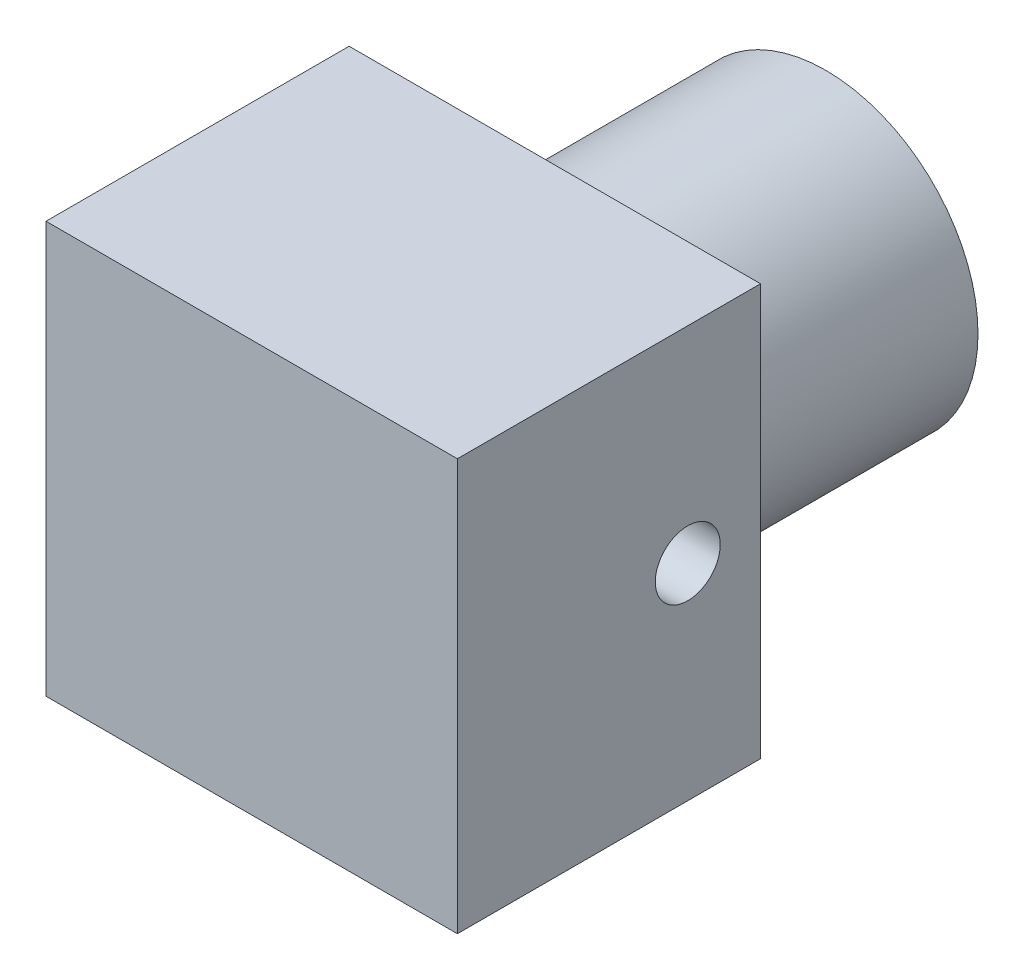
SolidWorks part; units mm, degrees
ref_plane "前视基准面" through (0, 0, 0) normal (0, 0, 1) x (1, 0, 0)
ref_plane "上视基准面" through (0, 0, 0) normal (0, 1, 0) x (1, 0, 0)
ref_plane "右视基准面" through (0, 0, 0) normal (1, 0, 0) x (0, 0, -1)
other "Configuration Table"
sketch "草图1" plane through (0, 0, 0) normal (0, 0, 1) x (1, 0, 0)
  circle A0 centre (0, 0) radius 7.025
  dimension "D1" = 14.05
extrude "凸台-拉伸1" add sketch "草图1" along normal blind 12.52
sketch "草图2" plane through (0, 0, 12.52) normal (0, 0, 1) x (1, 0, 0)
  line L0 (0, 0) -> (9.5, 9.5) construction
  line L1 (-9.5, -9.5) -> (9.5, -9.5)
  line L2 (-9.5, -9.5) -> (-9.5, 9.5)
  line L3 (-9.5, 9.5) -> (9.5, 9.5)
  line L4 (9.5, -9.5) -> (9.5, 9.5)
  line L5 (-9.5, -9.5) -> (-4.9674, -4.9674) construction
  line L6 (-9.5, 9.5) -> (0, 0) construction
  line L7 (4.9674, -4.9674) -> (9.5, -9.5) construction
  dimension "D2" = 19
  dimension "D3" = 19
extrude "凸台-拉伸2" add sketch "草图2" along normal blind 14
sketch "草图3" plane through (-9.5, 0, 0) normal (-1, 0, 0) x (0, 0, 1)
  line L0 (12.52, 0) -> (15.88, 0)
  line L4 (12.52, 9.5) -> (12.52, -9.5)
  line L5 (12.52, -9.5) -> (26.52, -9.5)
  line L6 (26.52, -9.5) -> (26.52, 9.5)
  line L7 (26.52, 9.5) -> (12.52, 9.5)
  line L8 (12.52, 9.5) -> (12.52, -9.5)
  line L9 (12.52, -9.5) -> (26.52, -9.5)
  line L10 (26.52, -9.5) -> (26.52, 9.5)
  line L11 (26.52, 9.5) -> (12.52, 9.5)
  circle A0 centre (15.88, 0) radius 1.5
  point P7 (14.38, 0)
  dimension "D3" = 3
  dimension "D2" = 1.86
  dimension "D1" = 0
extrude "切除-拉伸1" cut sketch "草图3" against normal through all
